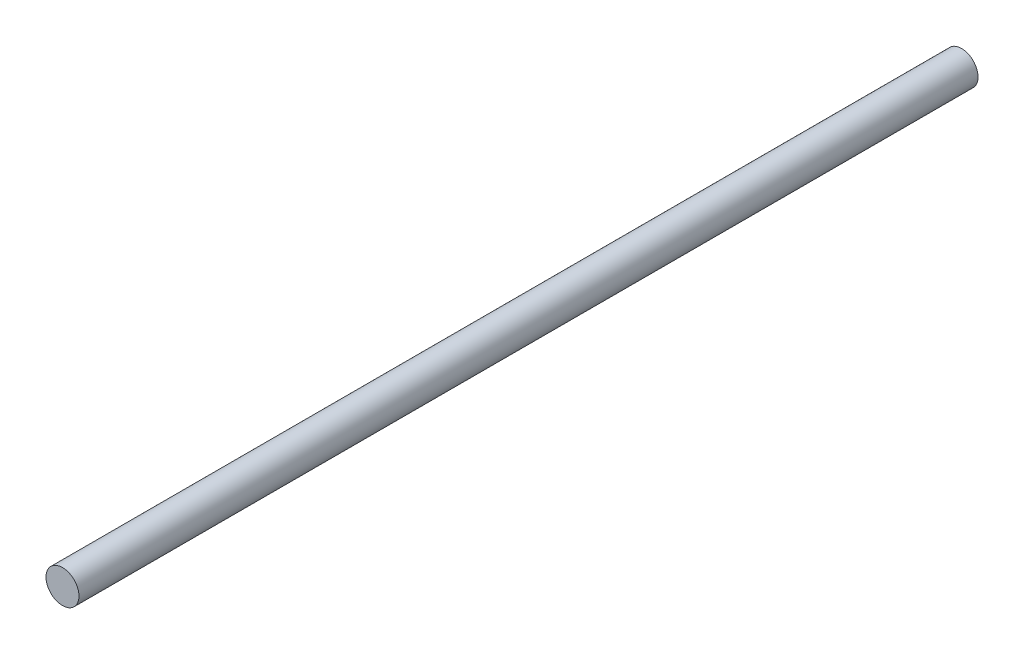
SolidWorks part; units mm, degrees
material "Copper"
ref_plane "Front Plane" through (0, 0, 0) normal (0, 0, 1) x (1, 0, 0)
ref_plane "Top Plane" through (0, 0, 0) normal (0, 1, 0) x (1, 0, 0)
ref_plane "Right Plane" through (0, 0, 0) normal (1, 0, 0) x (0, 0, -1)
sketch "Sketch1" plane through (0, 0, 0) normal (0, 0, 1) x (1, 0, 0)
  circle A0 centre (0, 0) radius 0.6985
  dimension "D1" = 1.397
extrude "Extrude1" add sketch "Sketch1" along normal blind 38.1
